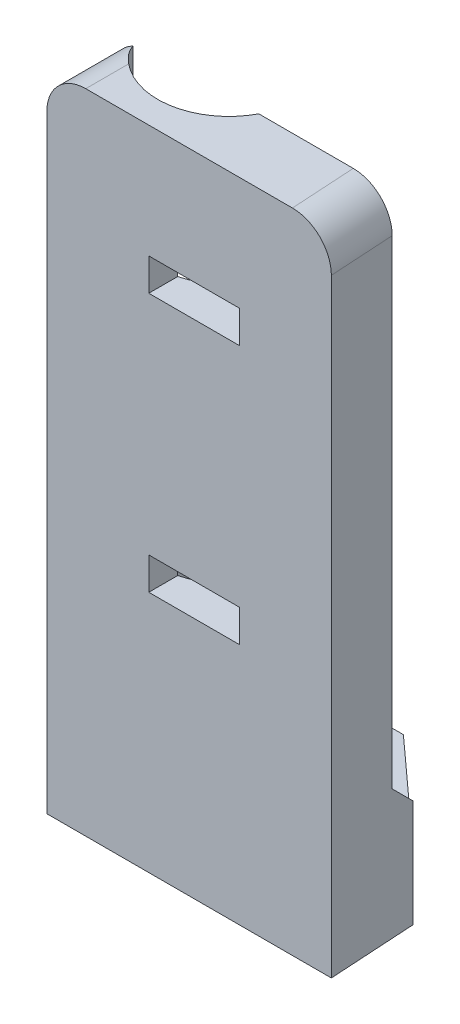
SolidWorks part; units mm, degrees
ref_plane "Front Plane" through (0, 0, 0) normal (0, 0, 1) x (1, 0, 0)
ref_plane "Top Plane" through (0, 0, 0) normal (0, 1, 0) x (1, 0, 0)
ref_plane "Right Plane" through (0, 0, 0) normal (1, 0, 0) x (0, 0, -1)
sketch "Sketch1" plane through (0, 0, 0) normal (0, 1, 0) x (1, 0, 0)
  line L0 (0, 0) -> (0, -3.25) construction
  line L1 (-5.3208, 8) -> (-22.469, -7.56)
  line L3 (-11.3345, 0) -> (11.3345, 0) construction
  line L4 (5.3208, 8) -> (22.469, -7.56)
  line L5 (-22.469, -7.56) -> (22.469, -7.56)
  line L6 (-5.3208, 8) -> (5.3208, 8)
  circle A0 centre (0, 0) radius 3.25
  dimension "D1" = 6.5
  dimension "D2" = 42.22
  dimension "D3" = 7.56
  dimension "D4" = 9.5
  dimension "D5" = 8
extrude "Boss-Extrude1" add sketch "Sketch1" along normal blind 50
chamfer "Chamfer4" distance 7 distance2 10 1 edges at (22.469, 25, 7.56)
sketch "Sketch2" plane through (0, 50, 0) normal (0, 1, 0) x (1, 0, 0)
  circle A0 centre (0, 0) radius 5.5
  dimension "D1" = 11
extrude "Cut-Extrude1" cut sketch "Sketch2" along direction (0, -1, 0) on the side against the normal offset from surface (45 mm away) 5
sketch "Sketch4" plane through (0, 0, 0) normal (0, -1, 0) x (1, 0, 0)
  line L0 (-6.5, 0) -> (-6.5, 8.4553)
  line L1 (0, -6.5) -> (12.1315, -6.5)
  line L2 (-6.5, 8.4553) -> (-18.0929, 18.5095)
  line L3 (-18.0929, 18.5095) -> (-27.844, 13.2665)
  line L4 (-27.844, 13.2665) -> (-26.2398, -3.9571)
  line L5 (-26.2398, -3.9571) -> (-22.0516, -11.7465)
  line L7 (12.1315, -6.5) -> (6.4453, -11.9042)
  line L8 (6.4453, -11.9042) -> (-22.0516, -11.7465)
  circle A1 centre (0, 0) radius 5.5 construction
  circle A2 centre (0, 0) radius 5.5 construction
  circle A3 centre (0, 0) radius 6.5 construction
  arc A4 (0, -6.5) -> (-6.5, 0) centre (0, 0) cw
  dimension "D1" = 1
extrude "Cut-Extrude3" cut sketch "Sketch4" against normal blind 50 and the other way through all
sketch "Sketch5" plane through (0, 50, 0) normal (0, 1, 0) x (1, 0, 0)
  line L0 (0, 0) -> (4.8679, -2.56)
  line L4 (-4.8679, -2.56) -> (0, 0)
  line L6 (-4.8679, -2.56) -> (-9.589, -2.56)
  line L7 (4.8679, -2.56) -> (20.4828, -2.56)
  line L8 (20.4828, -2.56) -> (8.2569, 8.38)
  line L9 (8.2569, 8.38) -> (1.3414, 8.38)
  line L10 (1.3414, 8.38) -> (-9.589, 8.38)
  line L11 (-9.589, 8.38) -> (-9.589, -2.56)
  line L13 (-6.5, -7.56) -> (15.469, -7.56) construction
  circle A0 centre (0, 0) radius 5.5 construction
  dimension "D1" = 5
extrude "Cut-Extrude4" cut sketch "Sketch5" against normal up to surface (45 mm away) up to face at (0, 5, -3.25)
chamfer "Chamfer5" distance 5 angle 45 2 edges at (10.0175, 5, 2.56) (-5.6839, 5, 2.56)
fillet "Fillet1" radius 3 2 edges at (15.3181, 50, 5.06) (-6.5, 50, 5.06)
sketch "Sketch6" plane through (0, 5, 0) normal (0, 1, 0) x (1, 0, 0)
  arc A0 (-4.9291, 2.44) -> (4.9291, 2.44) centre (0, 0) ccw construction
  circle A1 centre (0, 0) radius 3.25 construction
  circle A2 centre (0, 0) radius 5.5
  circle A3 centre (0, 0) radius 3.25
extrude "Boss-Extrude2" add sketch "Sketch6" along normal blind 11
sketch "Sketch9" plane through (0, 0, 7.56) normal (0, 0, 1) x (1, 0, 0)
  line L0 (-3.5, 50) -> (12.4636, 50) construction
  line L1 (1.3679, 41.25) -> (8.3679, 41.25)
  line L2 (1.3679, 41.25) -> (1.3679, 38.75)
  line L3 (1.3679, 38.75) -> (8.3679, 38.75)
  line L4 (8.3679, 41.25) -> (8.3679, 38.75)
  line L5 (1.3679, 21.25) -> (1.3679, 18.75)
  line L6 (1.3679, 21.25) -> (8.3679, 21.25)
  line L7 (8.3679, 21.25) -> (8.3679, 18.75)
  line L8 (1.3679, 18.75) -> (8.3679, 18.75)
  point P4 (8.3679, 40)
  point P7 (4.8679, 41.25)
  dimension "D1" = 2.5
  dimension "D2" = 7
  dimension "D3" = 10
  dimension "D4" = 2
extrude "Cut-Extrude5" cut sketch "Sketch9" against normal blind 15
